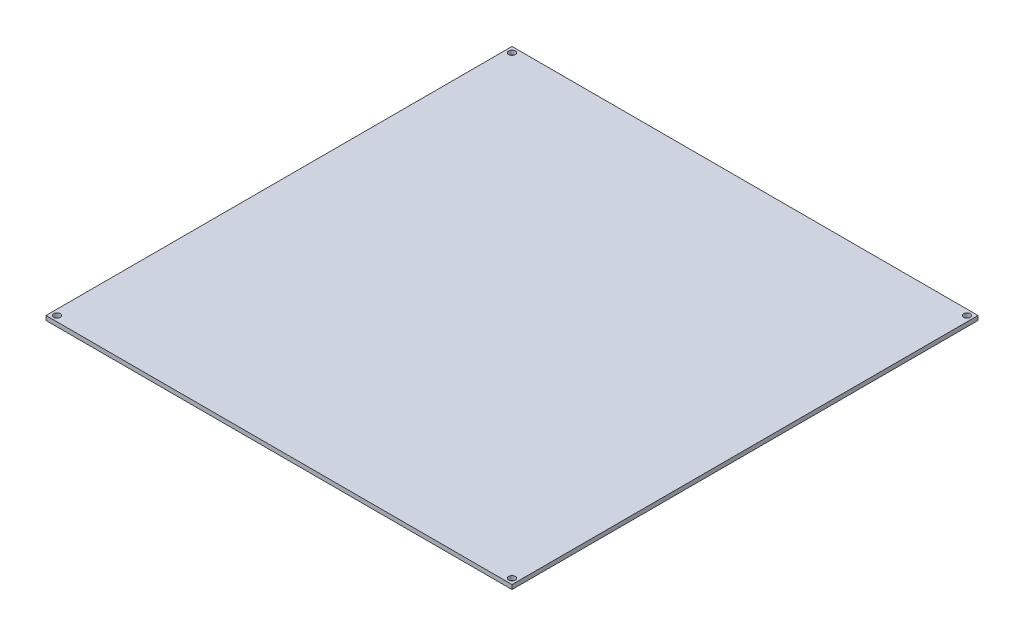
SolidWorks part; units mm, degrees
material "Custom Plastic"
ref_plane "Front Plane" through (0, 0, 0) normal (0, 0, 1) x (1, 0, 0)
ref_plane "Top Plane" through (0, 0, 0) normal (0, 1, 0) x (1, 0, 0)
ref_plane "Right Plane" through (0, 0, 0) normal (1, 0, 0) x (0, 0, -1)
sketch "Sketch1" plane through (0, 0, 0) normal (0, 1, 0) x (1, 0, 0)
  line L1 (-107, -107) -> (107, -107)
  line L2 (-107, -107) -> (-107, 107)
  line L3 (-107, 107) -> (107, 107)
  line L4 (107, -107) -> (107, 107)
  line L5 (-107, -107) -> (107, 107) construction
  line L6 (-107, 107) -> (107, -107) construction
  point P0 (0, 0)
  dimension "D1" = 214
  dimension "D2" = 214
extrude "Boss-Extrude1" add sketch "Sketch1" along normal blind 2
sketch "Sketch3" plane through (0, 2, 0) normal (0, 1, 0) x (1, 0, 0)
  circle A0 centre (-104.5, 104.5) radius 1.5
  circle A1 centre (104.5, 104.5) radius 1.5
  circle A2 centre (104.5, -104.5) radius 1.5
  circle A3 centre (-104.5, -104.5) radius 1.5
  point P0 (0, 0)
extrude "Cut-Extrude1" cut sketch "Sketch3" against normal through all both and the other way through all
